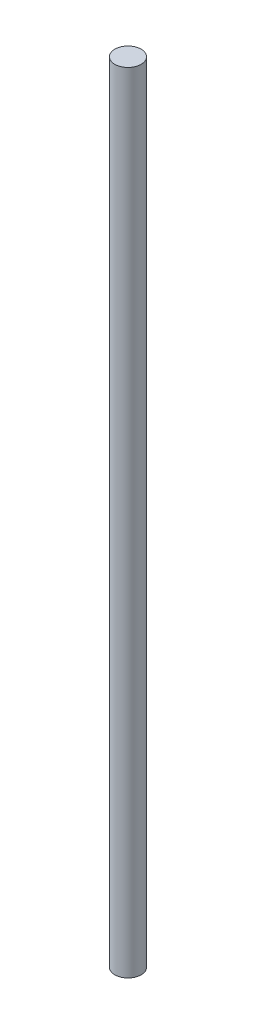
SolidWorks part; units mm, degrees
ref_plane "Front Plane" through (0, 0, 0) normal (0, 0, 1) x (1, 0, 0)
ref_plane "Top Plane" through (0, 0, 0) normal (0, 1, 0) x (1, 0, 0)
ref_plane "Right Plane" through (0, 0, 0) normal (1, 0, 0) x (0, 0, -1)
sketch "Sketch1" plane through (0, 0, 0) normal (0, 1, 0) x (1, 0, 0)
  circle A0 centre (0, 0) radius 2.5
  dimension "D1" = 5
extrude "Boss-Extrude1" add sketch "Sketch1" along normal mid plane 150
